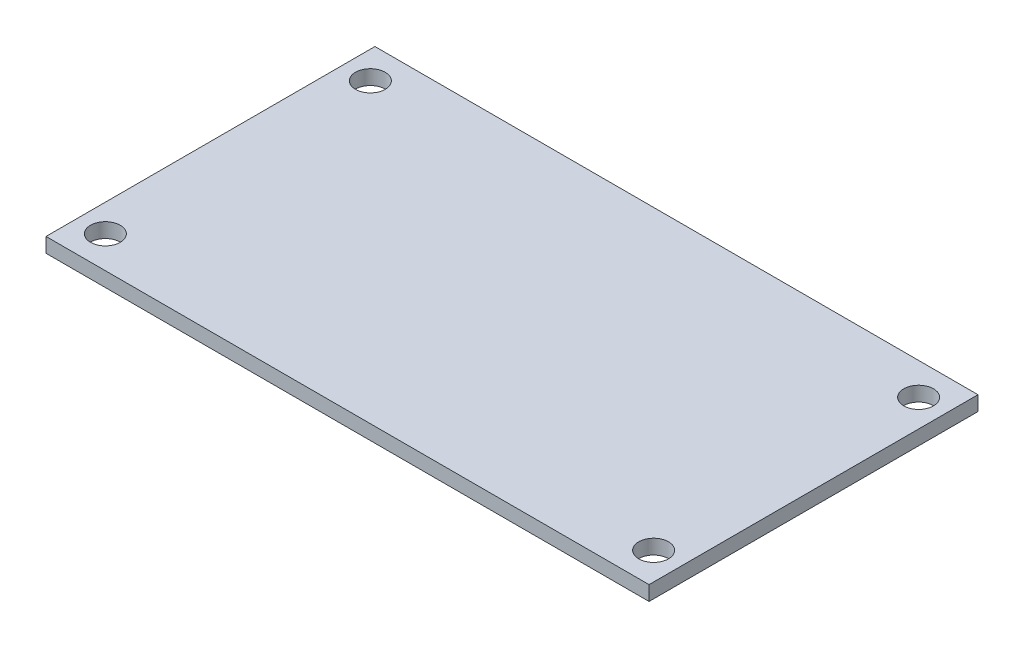
SolidWorks part; units mm, degrees
ref_plane "Front Plane" through (0, 0, 0) normal (0, 0, 1) x (1, 0, 0)
ref_plane "Top Plane" through (0, 0, 0) normal (0, 1, 0) x (1, 0, 0)
ref_plane "Right Plane" through (0, 0, 0) normal (1, 0, 0) x (0, 0, -1)
sketch "Sketch1" plane through (0, 0, 0) normal (0, 1, 0) x (1, 0, 0)
  line L0 (33, 36) -> (33, 0) construction
  line L1 (0, 0) -> (66, 0)
  line L2 (0, 0) -> (0, 36)
  line L3 (0, 36) -> (66, 36)
  line L4 (66, 0) -> (66, 36)
  line L6 (3, 32.5) -> (63, 32.5) construction
  line L7 (3, 32.5) -> (3, 3.5) construction
  line L8 (3, 3.5) -> (63, 3.5) construction
  line L9 (63, 32.5) -> (63, 3.5) construction
  line L10 (3, 32.5) -> (63, 3.5) construction
  line L11 (3, 3.5) -> (63, 32.5) construction
  circle A0 centre (3, 32.5) radius 1.625
  circle A1 centre (3, 3.5) radius 1.625
  circle A2 centre (63, 3.5) radius 1.625
  circle A3 centre (63, 32.5) radius 1.625
  point P7 (33, 18)
  dimension "D5" = 3.25
  dimension "D1" = 36
  dimension "D2" = 66
  dimension "D3" = 29
  dimension "D4" = 60
extrude "Boss-Extrude1" add sketch "Sketch1" along normal blind 1.6
